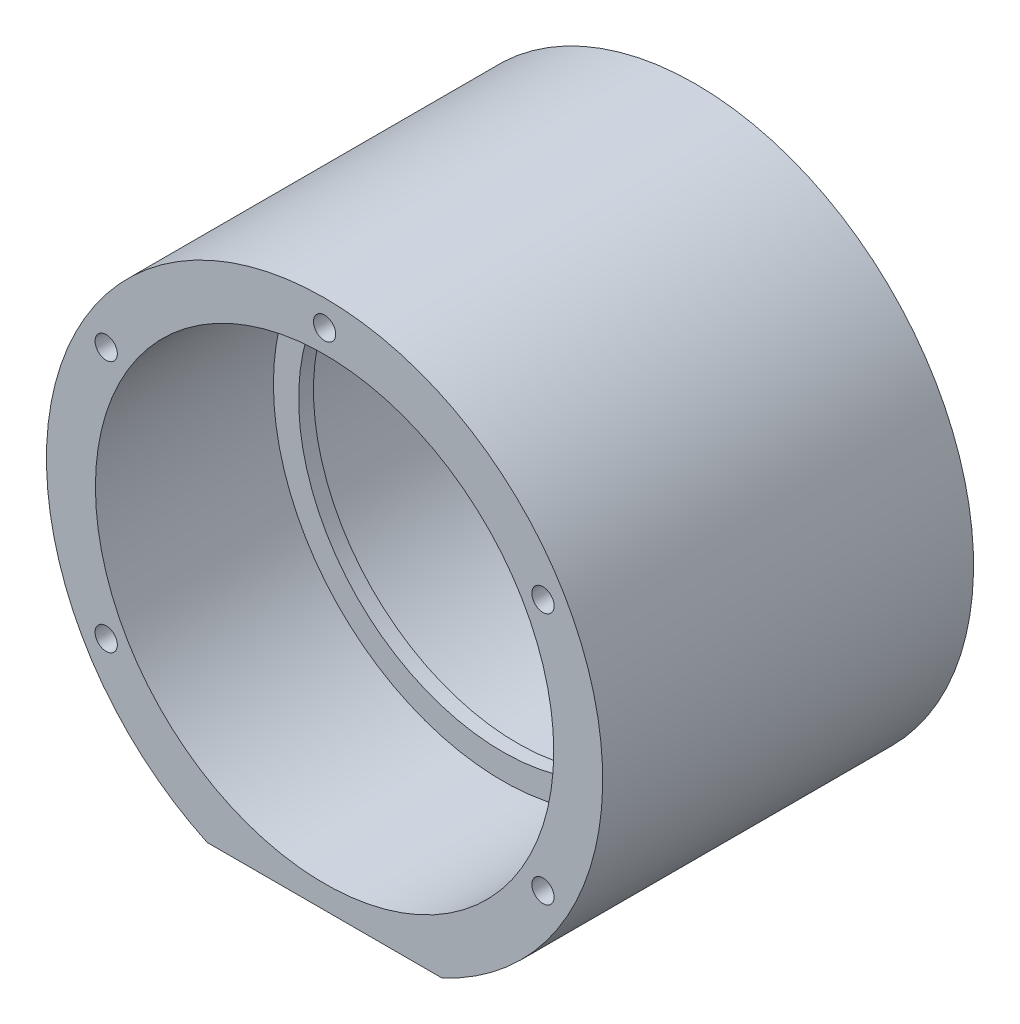
SolidWorks part; units mm, degrees
ref_plane "Front Plane" through (0, 0, 0) normal (0, 0, 1) x (1, 0, 0)
ref_plane "Top Plane" through (0, 0, 0) normal (0, 1, 0) x (1, 0, 0)
ref_plane "Right Plane" through (0, 0, 0) normal (1, 0, 0) x (0, 0, -1)
sketch "Sketch1" plane through (0, 0, 0) normal (0, 0, 1) x (1, 0, 0)
  line L0 (-15.8193, -34) -> (15.8193, -34)
  line L1 (0, 34) -> (0, 0) construction
  arc A0 (15.8193, -34) -> (-15.8193, -34) centre (0, 0) ccw
  circle A1 centre (0, 0) radius 30.9
  circle A2 centre (0, 34) radius 1.5
  circle A3 centre (29.4449, 17) radius 1.5
  circle A4 centre (29.4449, -17) radius 1.5
  circle A6 centre (-29.4449, -17) radius 1.5
  circle A7 centre (-29.4449, 17) radius 1.5
  arc A8 (-1.5, -34) -> (1.5, -34) centre (0, -34) ccw [skipped]
  point P20 (0, 0)
  dimension "D1" = 61.8
  dimension "D2" = 75
  dimension "D5" = 3
  dimension "D3" = 34
  dimension "D4" = 34
  dimension "D6" = 6
extrude "Boss-Extrude1" add sketch "Sketch1" along normal blind 50
ref_plane "Plane1" through (0, 0, 25) normal (0, 0, 1) x (1, 0, 0)
sketch "Sketch2" plane through (0, 0, 25) normal (0, 0, 1) x (1, 0, 0)
  circle A0 centre (0, 0) radius 30.9
  circle A1 centre (0, 0) radius 27.5
  dimension "D1" = 55
extrude "Boss-Extrude2" add sketch "Sketch2" along normal blind 1 and the other way blind 1
